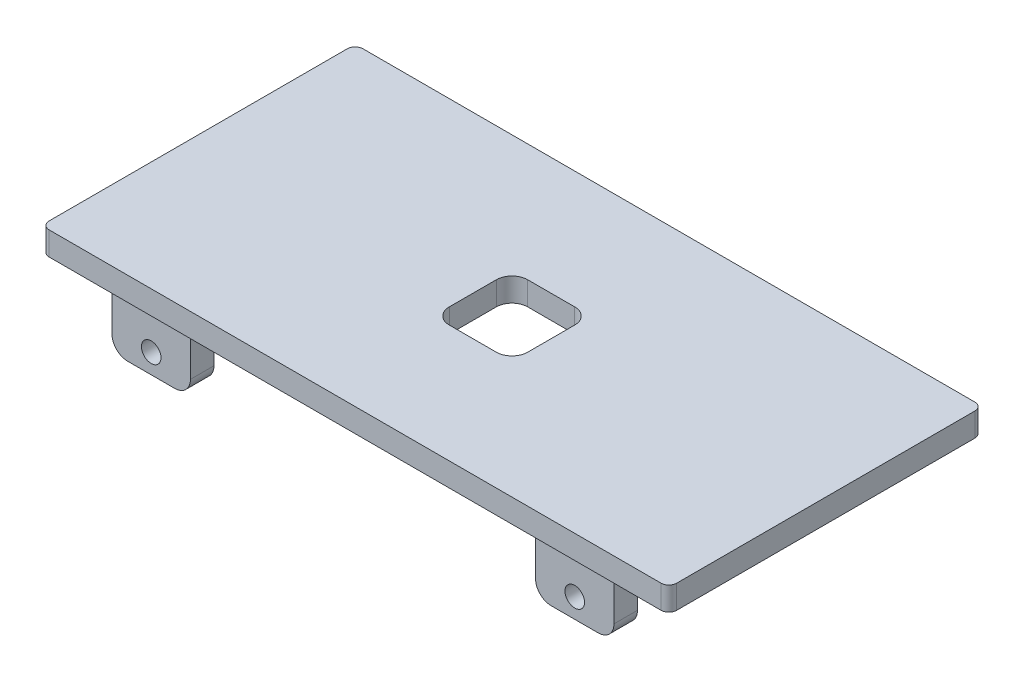
SolidWorks part; units mm, degrees
ref_plane "Front Plane" through (0, 0, 0) normal (0, 0, 1) x (1, 0, 0)
ref_plane "Top Plane" through (0, 0, 0) normal (0, 1, 0) x (1, 0, 0)
ref_plane "Right Plane" through (0, 0, 0) normal (1, 0, 0) x (0, 0, -1)
sketch "Sketch1" plane through (0, 0, 0) normal (0, 1, 0) x (1, 0, 0)
  line L1 (0, 0) -> (800, 0)
  line L2 (0, 0) -> (0, 400)
  line L3 (0, 400) -> (800, 400)
  line L4 (800, 0) -> (800, 400)
  dimension "D1" = 400
  dimension "D2" = 800
extrude "Boss-Extrude1" add sketch "Sketch1" along normal blind 30
sketch "Sketch3" plane through (0, 30, 0) normal (0, 1, 0) x (1, 0, 0)
  line L0 (800, 0) -> (800, 400) construction
  line L1 (0, 0) -> (800, 0) construction
  line L2 (350, 250) -> (350, 150)
  line L3 (350, 150) -> (450, 150)
  line L4 (450, 150) -> (450, 250)
  line L5 (450, 250) -> (350, 250)
  point P0 (400, 150)
  point P3 (350, 200)
  dimension "D1" = 100
  dimension "D2" = 100
  dimension "D3" = 400
  dimension "D4" = 200
extrude "Cut-Extrude1" cut sketch "Sketch3" against normal through all
fillet "Fillet1" radius 20 4 edges at (450, 15, -250) (350, 15, -250) (450, 15, -150) (350, 15, -150)
sketch "Sketch4" plane through (0, 0, 0) normal (0, -1, 0) x (1, 0, 0)
  line L0 (80, -10) -> (80, -40)
  line L1 (80, -40) -> (180, -40)
  line L2 (180, -40) -> (180, -10)
  line L3 (180, -10) -> (80, -10)
  line L8 (400, -400) -> (400, 0) construction
  line L9 (800, -400) -> (0, -400) construction
  line L10 (0, 0) -> (800, 0) construction
  line L11 (0, -400) -> (0, 0) construction
  line L12 (0, -200) -> (800, -200) construction
  line L13 (800, 0) -> (800, -400) construction
  line L14 (620, -10) -> (720, -10)
  line L15 (620, -40) -> (620, -10)
  line L16 (720, -40) -> (620, -40)
  line L17 (720, -10) -> (720, -40)
  line L18 (720, -360) -> (620, -360)
  line L19 (720, -390) -> (720, -360)
  line L20 (620, -390) -> (720, -390)
  line L21 (620, -360) -> (620, -390)
  line L22 (180, -390) -> (80, -390)
  line L23 (180, -360) -> (180, -390)
  line L24 (80, -360) -> (180, -360)
  line L25 (80, -390) -> (80, -360)
  dimension "D1" = 100
  dimension "D2" = 30
  dimension "D3" = 10
  dimension "D4" = 80
extrude "Boss-Extrude2" add sketch "Sketch4" along normal blind 75
sketch "Sketch5" plane through (0, 0, -10) normal (0, 0, 1) x (1, 0, 0)
  line L0 (180, -75) -> (80, -75) construction
  line L1 (180, -75) -> (180, 0) construction
  circle A0 centre (130, -50) radius 12.5
  dimension "D1" = 25
  dimension "D2" = 25
  dimension "D3" = 50
extrude "Cut-Extrude2" cut sketch "Sketch5" against normal through all
sketch "Sketch6" plane through (0, 0, -10) normal (0, 0, 1) x (1, 0, 0)
  line L0 (720, -75) -> (620, -75) construction
  line L1 (620, -75) -> (620, 0) construction
  circle A0 centre (670, -50) radius 12.5
  dimension "D1" = 25
  dimension "D2" = 25
  dimension "D3" = 50
extrude "Cut-Extrude3" cut sketch "Sketch6" against normal through all
fillet "Fillet2" radius 20 8 edges at (180, -75, -25) (80, -75, -25) (180, -75, -375) (80, -75, -375) (620, -75, -25) (720, -75, -25) (620, -75, -375) (720, -75, -375)
fillet "Fillet3" radius 10 4 edges at (800, 15, 0) (800, 15, -400) (0, 15, -400) (0, 15, 0)
